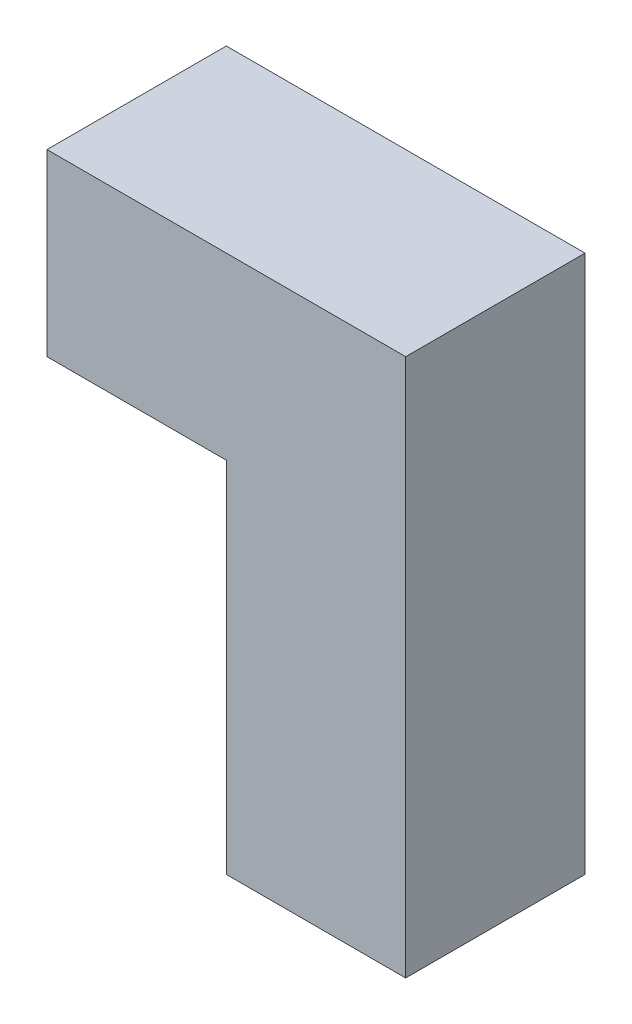
SolidWorks part; units mm, degrees
ref_plane "Front Plane" through (0, 0, 0) normal (1, 0, 0) x (0, 1, 0)
ref_plane "Top Plane" through (0, 0, 0) normal (0, 0, 1) x (0, 1, 0)
ref_plane "Right Plane" through (0, 0, 0) normal (0, 1, 0) x (-1, 0, 0)
sketch "Sketch1" plane through (0, 0, 0) normal (0, 0, 1) x (0, 1, 0)
  line L1 (-45, -30) -> (45, -30)
  line L2 (-45, -30) -> (-45, 30)
  line L3 (-45, 30) -> (45, 30)
  line L4 (45, -30) -> (45, 30)
  line L5 (-45, -30) -> (45, 30) construction
  line L6 (-45, 30) -> (45, -30) construction
  point P0 (0, 0)
  dimension "D1" = 90
  dimension "D2" = 60
extrude "Boss-Extrude1" add sketch "Sketch1" along normal mid plane 30
sketch "Sketch2" plane through (0, 0, 15) normal (0, 0, 1) x (1, 0, 0)
  line L0 (0, 15) -> (0, -15)
  line L2 (0, 15) -> (-30, 15)
  line L3 (-30, 45) -> (-30, -45) construction
  line L4 (0, -45) -> (0, -15)
  line L5 (-30, -45) -> (30, -45) construction
  line M4 (-30, 45) -> (-30, -45)
  line M5 (-30, -45) -> (30, -45)
  dimension "D1" = 60
extrude "Cut-Extrude1" cut sketch "Sketch2" against normal through all contours L4 L0 L2 M5 M4
